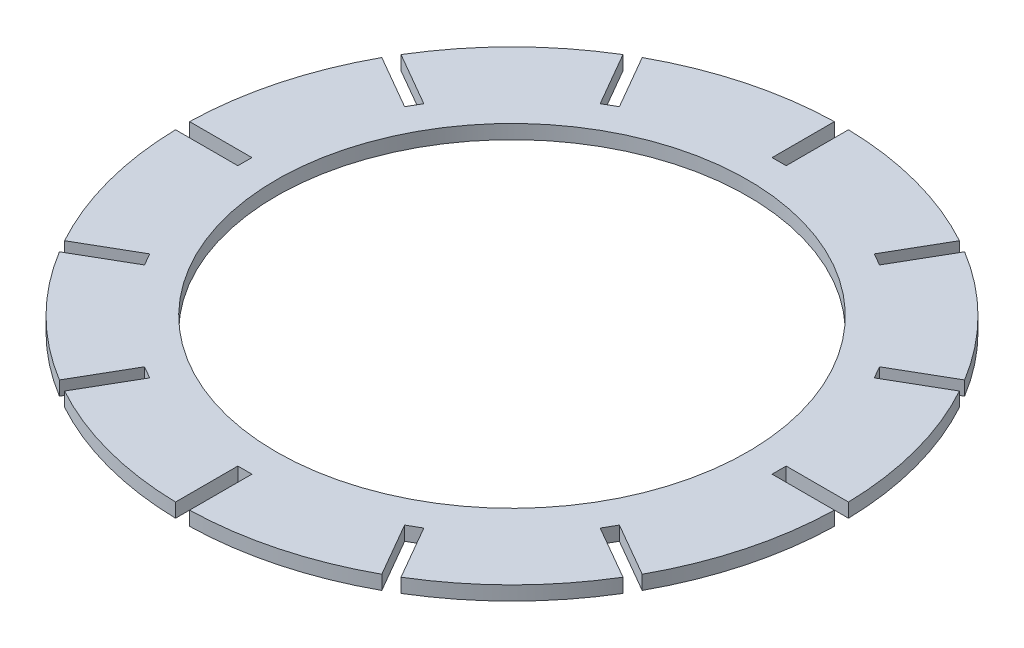
SolidWorks part; units mm, degrees
ref_plane "Front Plane" through (0, 0, 0) normal (0, 0, 1) x (1, 0, 0)
ref_plane "Top Plane" through (0, 0, 0) normal (0, 1, 0) x (1, 0, 0)
ref_plane "Right Plane" through (0, 0, 0) normal (1, 0, 0) x (0, 0, -1)
sketch "Sketch1" plane through (0, 0, 0) normal (0, 1, 0) x (1, 0, 0)
  circle A0 centre (0, 0) radius 50.25
  circle A1 centre (0, 0) radius 70.25
  point P2 (0, 0)
  dimension "D1" = 100.5
  dimension "D2" = 20
extrude "Boss-Extrude1" add sketch "Sketch1" along normal blind 3
sketch "Sketch2" plane through (0, 3, 0) normal (0, 1, 0) x (1, 0, 0)
  line L0 (0, 0) -> (-119.5598, 0) construction
  line L2 (-56.95, 1.5) -> (-70.25, 1.5)
  line L3 (-56.95, 1.5) -> (-56.95, -1.5)
  line L4 (-56.95, -1.5) -> (-70.25, -1.5)
  line L5 (-70.25, 1.5) -> (-70.25, -1.5)
  line L6 (-56.95, 1.5) -> (-70.25, -1.5) construction
  line L7 (-56.95, -1.5) -> (-70.25, 1.5) construction
  circle A0 centre (0, 0) radius 70.25 construction
  point P2 (-70.25, 0)
  point P4 (-62.1076, 0)
  point P5 (-63.6, 0)
  point P12 (0, 0)
  dimension "D1" = 3
  dimension "D2" = 13.3
extrude "Cut-Extrude1" cut sketch "Sketch2" against normal blind 3
pattern_circular "CirPattern1" count 12 over 360 about axis through (0, 0, 0) along (0, 1, 0) of "Cut-Extrude1"
